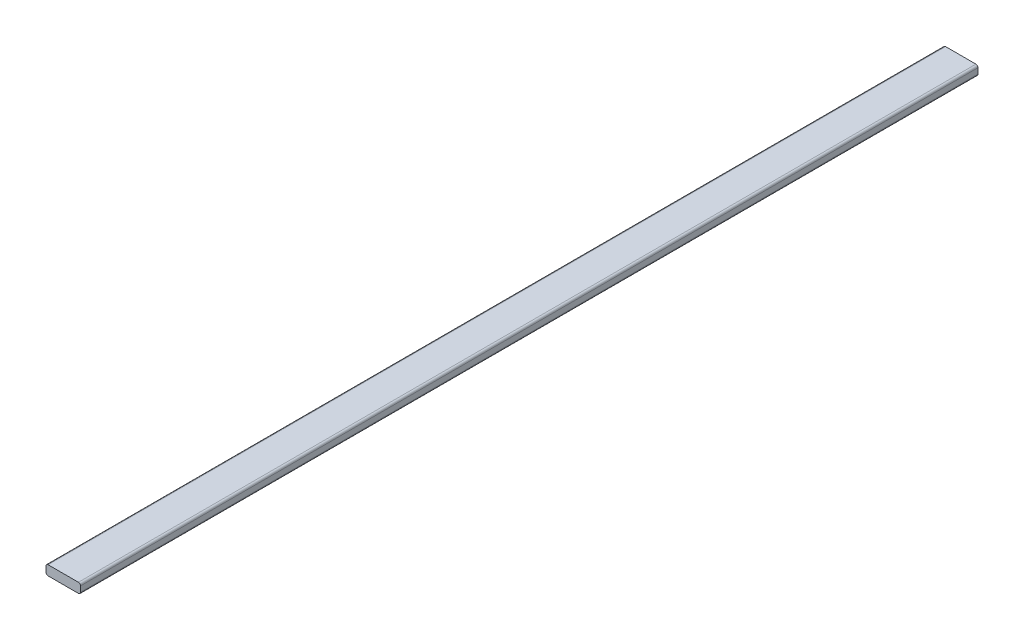
SolidWorks part; units mm, degrees
ref_plane "Front" through (0, 0, 0) normal (0, 0, 1) x (1, 0, 0)
ref_plane "Top" through (0, 0, 0) normal (0, 1, 0) x (1, 0, 0)
ref_plane "Right" through (0, 0, 0) normal (1, 0, 0) x (0, 0, -1)
sketch "Sketch2" plane through (0, 0, 0) normal (0, 0, 1) x (1, 0, 0)
  line L0 (0, 0) -> (12.7, 0)
  line L1 (12.7, 0) -> (12.7, 3.556)
  line L2 (12.7, 3.556) -> (0, 3.556)
  line L3 (0, 3.556) -> (0, 0)
  dimension "D1" = 12.7
  dimension "D2" = 3.556
extrude "Boss-Extrude1" add sketch "Sketch2" along normal blind 330.2
fillet "Fillet1" radius 0.762 4 edges at (12.7, 3.556, 165.1) (12.7, 0, 165.1) (0, 0, 165.1) (0, 3.556, 165.1)
